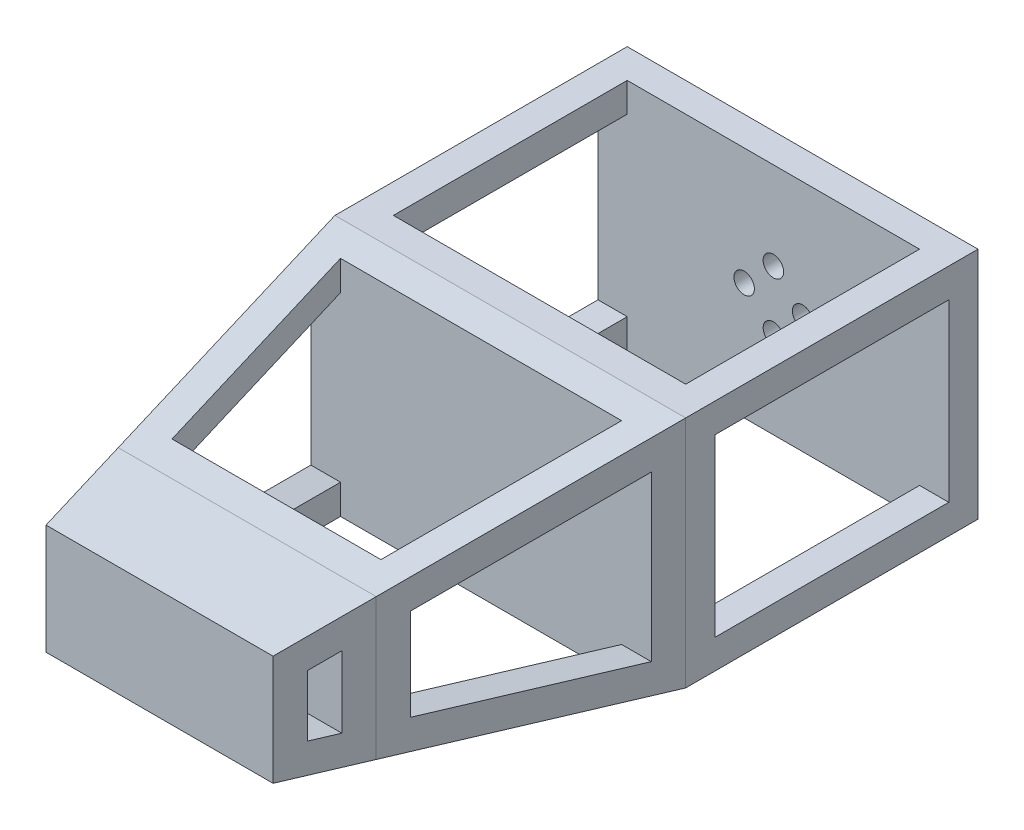
SolidWorks part; units mm, degrees
material "ABS"
ref_plane "Front Plane" through (0, 0, 0) normal (0, 0, 1) x (1, 0, 0)
ref_plane "Top Plane" through (0, 0, 0) normal (0, 1, 0) x (1, 0, 0)
ref_plane "Right Plane" through (0, 0, 0) normal (1, 0, 0) x (0, 0, -1)
sketch "Sketch1" plane through (0, 0, 0) normal (0, 0, 1) x (1, 0, 0)
  line L1 (-30, 20) -> (30, 20)
  line L2 (-30, 20) -> (-30, -20)
  line L3 (-30, -20) -> (30, -20)
  line L4 (30, 20) -> (30, -20)
  line L5 (-30, 20) -> (30, -20) construction
  line L6 (-30, -20) -> (30, 20) construction
  point P0 (0, 0)
  dimension "D1" = 60
  dimension "D2" = 40
extrude "Boss-Extrude1" add sketch "Sketch1" along normal blind 50
sketch "Sketch2" plane through (0, 0, 50) normal (0, 0, 1) x (1, 0, 0)
  line L1 (-25, 15) -> (25, 15)
  line L2 (-25, 15) -> (-25, -15)
  line L3 (-25, -15) -> (25, -15)
  line L4 (25, 15) -> (25, -15)
  line L5 (-25, 15) -> (25, -15) construction
  line L6 (-25, -15) -> (25, 15) construction
  point P0 (0, 0)
  dimension "D1" = 50
  dimension "D2" = 30
extrude "Cut-Extrude1" cut sketch "Sketch2" against normal blind 45
sketch "Sketch3" plane through (0, 20, 0) normal (0, 1, 0) x (1, 0, 0)
  line L0 (-30, -50) -> (-30, 0) construction
  line L5 (-25, -5) -> (25, -5)
  line L6 (-25, -5) -> (-25, -45)
  line L7 (-25, -45) -> (25, -45)
  line L8 (25, -5) -> (25, -45)
  line L9 (-25, -5) -> (25, -45) construction
  line L10 (-25, -45) -> (25, -5) construction
  line L11 (30, 0) -> (-30, 0) construction
  point P0 (0, -25)
  dimension "D1" = 50
  dimension "D2" = 5
  dimension "D3" = 40
  dimension "D4" = 5
extrude "Cut-Extrude2" cut sketch "Sketch3" against normal blind 45
sketch "Sketch4" plane through (30, 0, 0) normal (1, 0, 0) x (0, 0, -1)
  line L0 (-50, -20) -> (-50, 20) construction
  line L1 (-45, 15) -> (-5, 15)
  line L2 (-45, 15) -> (-45, -15)
  line L3 (-45, -15) -> (-5, -15)
  line L4 (-5, 15) -> (-5, -15)
  line L5 (-45, 15) -> (-5, -15) construction
  line L6 (-45, -15) -> (-5, 15) construction
  line L7 (-50, -20) -> (0, -20) construction
  point P0 (-25, 0)
  dimension "D1" = 40
  dimension "D2" = 30
  dimension "D3" = 5
  dimension "D4" = 5
extrude "Cut-Extrude3" cut sketch "Sketch4" against normal through all
sketch "Sketch5" plane through (0, 0, 50) normal (0, 0, 1) x (1, 0, 0)
  line L1 (-30, 20) -> (30, 20)
  line L2 (-30, 20) -> (-30, -20)
  line L3 (-30, -20) -> (30, -20)
  line L4 (30, 20) -> (30, -20)
  line L5 (-30, 20) -> (30, -20) construction
  line L6 (-30, -20) -> (30, 20) construction
  point P0 (0, 0)
extrude "Boss-Extrude2" add sketch "Sketch5" along normal blind 45 draft 10
sketch "Sketch6" plane through (0, 20, 95.7674) normal (0, -1, 0) x (1, 0, 0)
  line L4 (-24.0412, -40.7674) -> (24.0412, -40.7674)
  line L6 (-24.0412, -40.7674) -> (24.0412, -40.7674)
  line L9 (-17.8698, -5.7674) -> (-24.0412, -40.7674)
  line L10 (17.8698, -5.7674) -> (-17.8698, -5.7674)
  line L11 (24.0412, -40.7674) -> (17.8698, -5.7674)
  line L13 (-17.8698, -5.7674) -> (-24.0412, -40.7674)
  line L14 (17.8698, -5.7674) -> (-17.8698, -5.7674)
  line L15 (24.0412, -40.7674) -> (17.8698, -5.7674)
  dimension "D1" = 5
extrude "Cut-Extrude6" cut sketch "Sketch6" along normal through all
sketch "Sketch9" plane through (30, 0, 94.0309) normal (-1, 0, 0) x (0, 0, 1)
  line L8 (-39.0309, 14.0412) -> (-39.0309, -14.0412)
  line L9 (-4.0309, 7.8698) -> (-39.0309, 14.0412)
  line L10 (-4.0309, -7.8698) -> (-4.0309, 7.8698)
  line L11 (-39.0309, -14.0412) -> (-4.0309, -7.8698)
  line L12 (-39.0309, 14.0412) -> (-39.0309, -14.0412)
  line L13 (-4.0309, 7.8698) -> (-39.0309, 14.0412)
  line L14 (-4.0309, -7.8698) -> (-4.0309, 7.8698)
  line L15 (-39.0309, -14.0412) -> (-4.0309, -7.8698)
  dimension "D1" = 5
extrude "Cut-Extrude7" cut sketch "Sketch9" along normal through all
sketch "Sketch10" plane through (0, 0, 95) normal (0, 0, 1) x (1, 0, 0)
  line L0 (-22.0653, -12.0653) -> (22.0653, -12.0653) construction
  line L1 (-22.0653, 12.0653) -> (22.0653, 12.0653)
  line L2 (-22.0653, 12.0653) -> (-22.0653, -12.0653)
  line L3 (-22.0653, -12.0653) -> (22.0653, -12.0653)
  line L4 (22.0653, 12.0653) -> (22.0653, -12.0653)
  line L5 (-22.0653, 12.0653) -> (22.0653, -12.0653) construction
  line L6 (-22.0653, -12.0653) -> (22.0653, 12.0653) construction
  line L7 (22.0653, -12.0653) -> (22.0653, 12.0653) construction
  point P0 (0, 0)
extrude "Boss-Extrude3" add sketch "Sketch10" along normal blind 15 draft 10 separate body
sketch "Sketch15" plane through (30, 0, 94.0309) normal (-1, 0, 0) x (0, 0, 1)
  line L12 (5.9691, 6.1065) -> (5.9691, -6.1065)
  line L13 (10.9691, 5.2249) -> (5.9691, 6.1065)
  line L14 (10.9691, -5.2249) -> (10.9691, 5.2249)
  line L15 (5.9691, -6.1065) -> (10.9691, -5.2249)
  line L16 (5.9691, 6.1065) -> (5.9691, -6.1065)
  line L17 (10.9691, 5.2249) -> (5.9691, 6.1065)
  line L18 (10.9691, -5.2249) -> (10.9691, 5.2249)
  line L19 (5.9691, -6.1065) -> (10.9691, -5.2249)
  dimension "D1" = 5
extrude "Cut-Extrude8" cut sketch "Sketch15" along normal through all
sketch "Sketch17" plane through (0, 0, 0) normal (0, 0, -1) x (-1, 0, 0)
  line L0 (0, -3.3011) -> (0, 3.824) construction
  line L1 (-2.2165, 0) -> (1.9569, 0) construction
  line L2 (30, -20) -> (-30, -20) construction
  circle A0 centre (-5, 0) radius 1.75
  circle A1 centre (0, 5) radius 1.75
  circle A2 centre (5, 0) radius 1.75
  circle A3 centre (0, -5) radius 1.75
  dimension "D1" = 3.5
  dimension "D3" = 3.5
  dimension "D4" = 20
  dimension "D5" = 5
  dimension "D2" = 5
extrude "Cut-Extrude10" cut sketch "Sketch17" against normal blind 10
